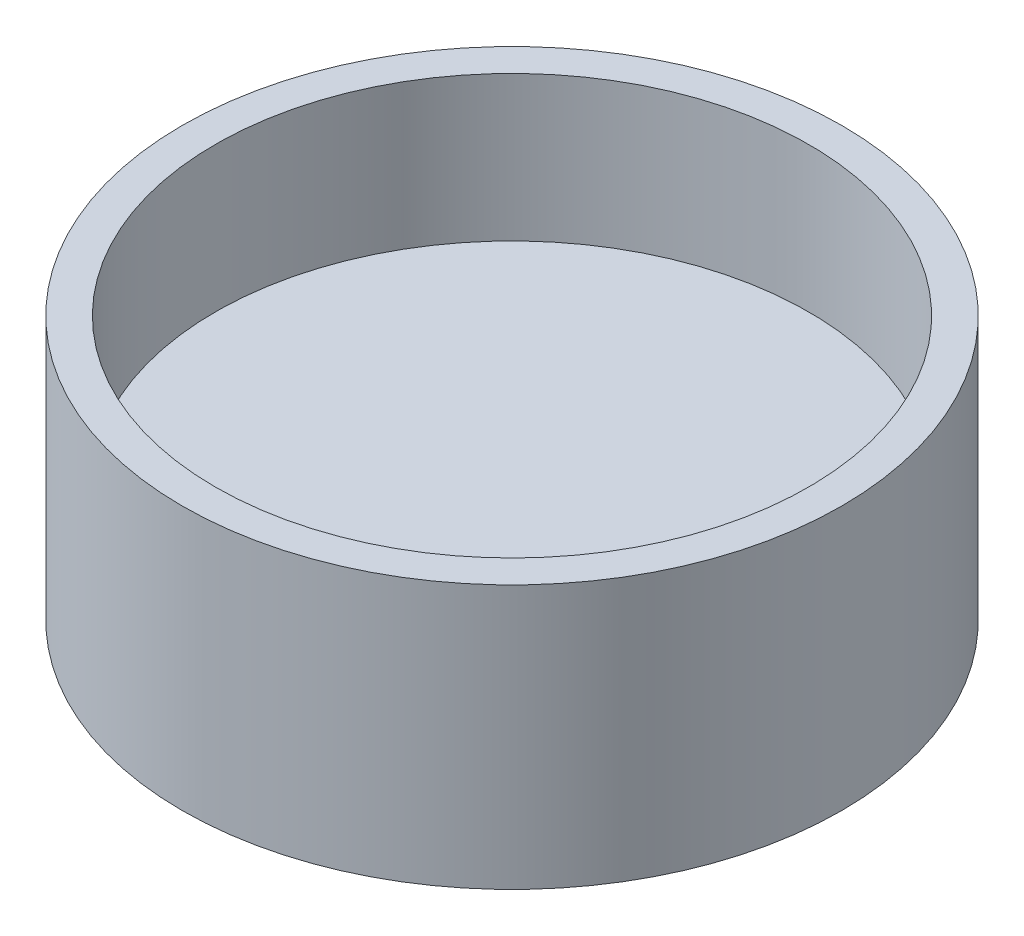
SolidWorks part; units mm, degrees
material "6061-T6 (SS)"
ref_plane "Front Plane" through (0, 0, 0) normal (0, 0, 1) x (1, 0, 0)
ref_plane "Top Plane" through (0, 0, 0) normal (0, 1, 0) x (1, 0, 0)
ref_plane "Right Plane" through (0, 0, 0) normal (1, 0, 0) x (0, 0, -1)
sketch "Sketch1" plane through (0, 0, 0) normal (0, 1, 0) x (1, 0, 0)
  circle A0 centre (0, 0) radius 12.5
  dimension "D1" = 25
extrude "Boss-Extrude1" add sketch "Sketch1" along normal mid plane 10
sketch "Sketch2" plane through (0, 5, 0) normal (0, 1, 0) x (1, 0, 0)
  circle A0 centre (0, 0) radius 11.25
  circle A1 centre (0, 0) radius 12.5 construction
  dimension "D1" = 1.25
extrude "Cut-Extrude1" cut sketch "Sketch2" against normal blind 5.5
sketch "Sketch3" plane through (0, -5, 0) normal (0, -1, 0) x (1, 0, 0)
  circle A1 centre (0, 0) radius 11.25
  circle A2 centre (0, 0) radius 11.25
  dimension "D1" = 0
extrude "Cut-Extrude2" cut sketch "Sketch3" against normal blind 3
